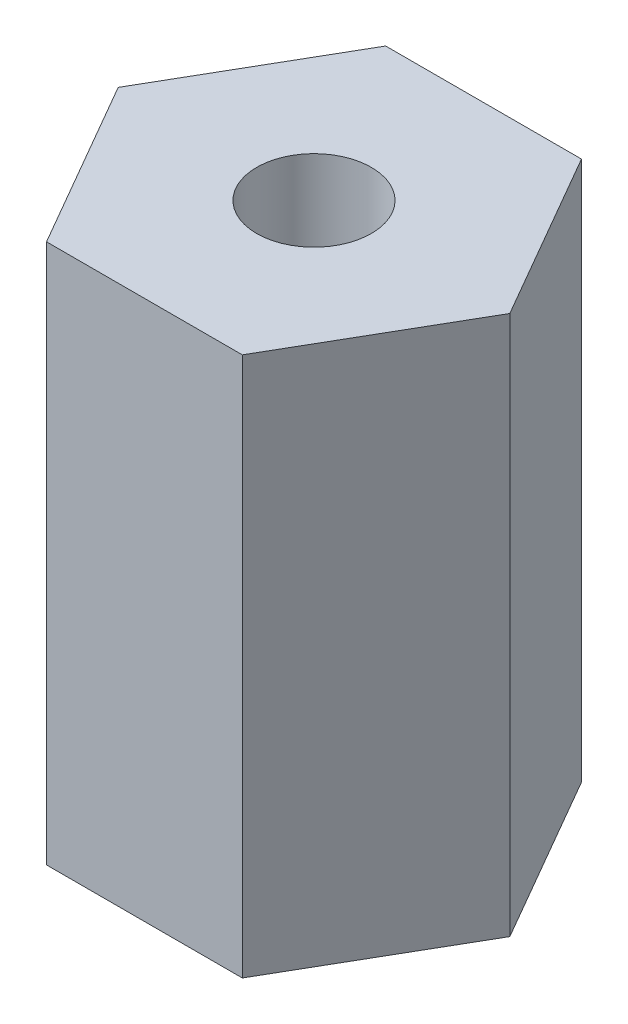
SolidWorks part; units mm, degrees
ref_plane "Front Plane" through (0, 0, 0) normal (0, 0, 1) x (1, 0, 0)
ref_plane "Top Plane" through (0, 0, 0) normal (0, 1, 0) x (1, 0, 0)
ref_plane "Right Plane" through (0, 0, 0) normal (1, 0, 0) x (0, 0, -1)
sketch "Sketch1" plane through (0, 0, 0) normal (0, 1, 0) x (1, 0, 0)
  line L1 (-4.6188, 0) -> (-2.3094, -4)
  line L2 (-2.3094, -4) -> (2.3094, -4)
  line L3 (2.3094, -4) -> (4.6188, 0)
  line L4 (4.6188, 0) -> (2.3094, 4)
  line L5 (2.3094, 4) -> (-2.3094, 4)
  line L6 (-2.3094, 4) -> (-4.6188, 0)
  circle A0 centre (0, 0) radius 4 construction
extrude "Boss-Extrude1" add sketch "Sketch1" along normal blind 12.73 contours L6 L1 L2 L3 L4 L5
sketch "Sketch3" plane through (0, 12.73, 0) normal (0, 1, 0) x (1, 0, 0)
  circle A0 centre (0, 0) radius 1.3525
extrude "Cut-Extrude1" cut sketch "Sketch3" against normal blind 6
sketch "Sketch4" plane through (0, 0, 0) normal (0, -1, 0) x (1, 0, 0)
  circle A0 centre (0, 0) radius 0.3535
extrude "Cut-Extrude2" cut sketch "Sketch4" against normal blind 1
